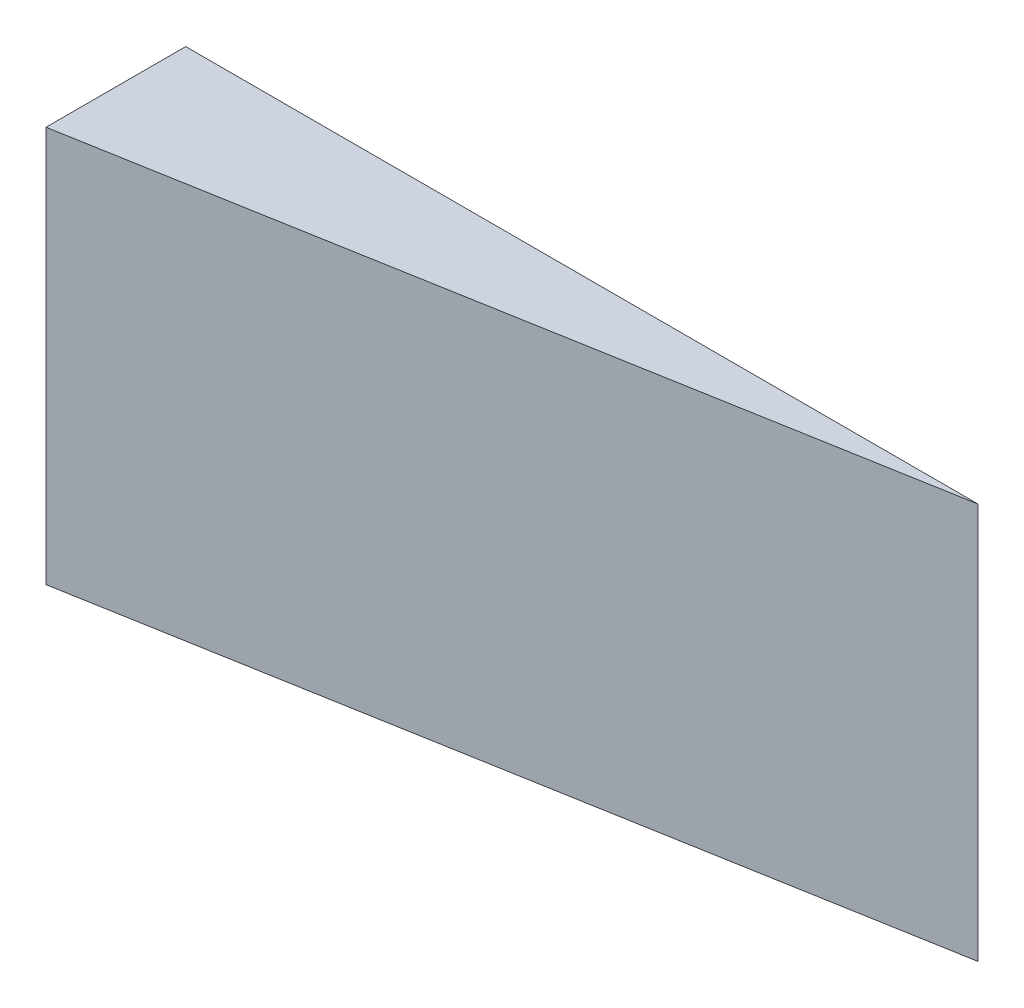
SolidWorks part; units mm, degrees
ref_plane "Přední rovina" through (0, 0, 0) normal (0, 0, 1) x (1, 0, 0)
ref_plane "Horní rovina" through (0, 0, 0) normal (0, 1, 0) x (1, 0, 0)
ref_plane "Pravá rovina" through (0, 0, 0) normal (1, 0, 0) x (0, 0, -1)
sketch "Sketch1" plane through (0, 0, 0) normal (0, 1, 0) x (1, 0, 0)
  line L0 (0, 0) -> (40, 0)
  line L1 (40, 0) -> (0, -7.0531)
  line L2 (0, -7.0531) -> (0, 0)
  point P4 (0, 0)
  point P5 (0, 0)
  dimension "D1" = 10
  dimension "D2" = 40
extrude "Boss-Extrude1" add sketch "Sketch1" along normal blind 20
